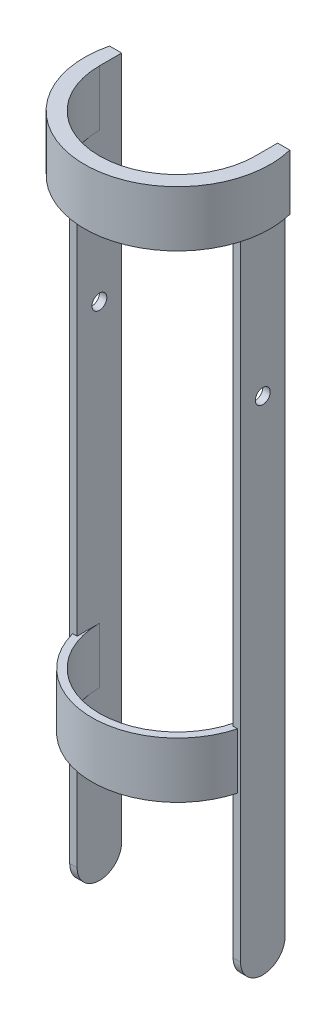
SolidWorks part; units mm, degrees
ref_plane "Front" through (0, 0, 0) normal (0, 0, 1) x (1, 0, 0)
ref_plane "Top" through (0, 0, 0) normal (0, 1, 0) x (1, 0, 0)
ref_plane "Right" through (0, 0, 0) normal (1, 0, 0) x (0, 0, -1)
sketch "草图1" plane through (0, 0, 0) normal (0, 1, 0) x (1, 0, 0)
  line L0 (-42, 0) -> (0, 0) construction
  line L1 (-46, 0) -> (-84.254, 0) construction
  line L2 (0, 0) -> (0, 41.4) construction
  line L5 (-46, 0) -> (-46, 12)
  line L6 (-46, 12) -> (-42, 12)
  line L7 (-42, 0) -> (-42, 12)
  line L11 (46, 0) -> (46, 12)
  line L12 (46, 12) -> (42, 12)
  line L13 (42, 0) -> (42, 12)
  arc A2 (-46, 0) -> (46, 0) centre (0, 0) ccw
  arc A3 (-42, 0) -> (42, 0) centre (0, 0) ccw
  dimension "D1" = 12
  dimension "D2" = 12
extrude "凸台-拉伸1" add sketch "草图1" along normal blind 30
sketch "草图2" plane through (0, 30, 0) normal (0, 1, 0) x (1, 0, 0)
  line L9 (-46, 12) -> (-42, 12)
  line L10 (-46, 12) -> (-46, -12)
  line L11 (-46, -12) -> (-42, -12)
  line L12 (-42, 12) -> (-42, -12)
  line L13 (46, 12) -> (42, 12)
  line L14 (46, 12) -> (46, -12)
  line L15 (46, -12) -> (42, -12)
  line L16 (42, 12) -> (42, -12)
  dimension "D1" = 24
  dimension "D2" = 4
  dimension "D3" = 4
  dimension "D4" = 24
extrude "凸台-拉伸2" add sketch "草图2" against normal blind 120
sketch "草图3" plane through (46, 0, 0) normal (1, 0, 0) x (0, 0, -1)
  line L2 (-12, -78) -> (-12, -98.5061)
  line L3 (-12, -98.5061) -> (12, -98.5061)
  line L4 (12, -78) -> (12, -98.5061)
  arc A0 (-12, -78) -> (12, -78) centre (0, -78) ccw
extrude "切除-拉伸1" cut sketch "草图3" against normal through all
sketch "草图4" plane through (0, 30, 0) normal (0, 1, 0) x (1, 0, 0)
  line L1 (46, 12) -> (42, 12)
  line L2 (46, 12) -> (46, -12)
  line L3 (46, -12) -> (42, -12)
  line L4 (42, 12) -> (42, -12)
  line L5 (-46, 12) -> (-42, 12)
  line L6 (-46, 12) -> (-46, -12)
  line L7 (-46, -12) -> (-42, -12)
  line L8 (-42, 12) -> (-42, -12)
  dimension "D1" = 4
  dimension "D2" = 24
  dimension "D3" = 4
  dimension "D4" = 24
extrude "凸台-拉伸3" add sketch "草图4" along normal blind 260
sketch "草图5" plane through (0, 290, 0) normal (0, 1, 0) x (1, 0, 0)
  line L0 (965.5016, 12) -> (42, 12) construction
  line L1 (-48.5386, 12) -> (-42, 12)
  line L2 (42, 12) -> (48.5386, 12)
  line L3 (-42, 12) -> (-42, 0)
  line L4 (-42, 12) -> (-56.8817, 12) construction
  line L5 (42, 12) -> (42, 0)
  line L6 (40.2492, 12) -> (-40.2492, 12) construction
  arc A0 (-42, 0) -> (42, 0) centre (0, 0) ccw
  arc A1 (-48.5386, 12) -> (48.5386, 12) centre (0, 0) ccw
extrude "凸台-拉伸4" add sketch "草图5" against normal blind 30
sketch "草图6" plane through (46, 0, 0) normal (1, 0, 0) x (0, 0, -1)
  line L0 (0, 260) -> (0, 132.2251) construction
  line L1 (-12, 260) -> (12, 260) construction
  line L2 (-12, 260) -> (12, 260) construction
  line L3 (12, 260) -> (12, -78) construction
  circle A0 centre (0, 180) radius 4
  dimension "D1" = 80
extrude "切除-拉伸2" cut sketch "草图6" against normal through all
